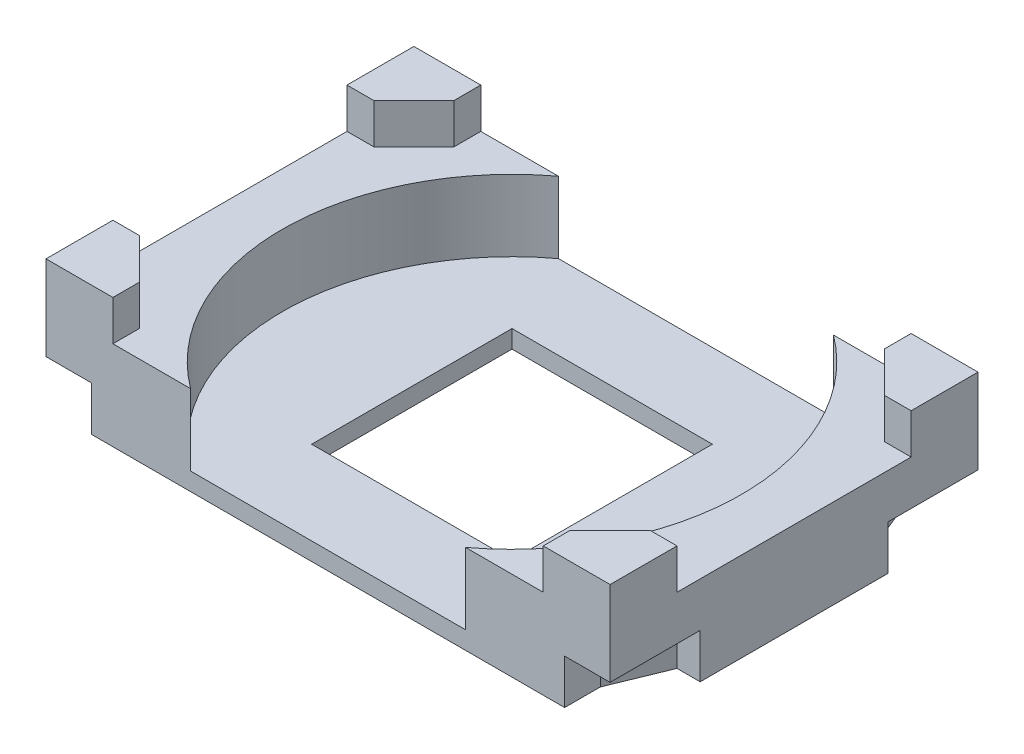
SolidWorks part; units mm, degrees
ref_plane "Спереди" through (0, 0, 0) normal (0, 0, 1) x (1, 0, 0)
ref_plane "Сверху" through (0, 0, 0) normal (0, 1, 0) x (1, 0, 0)
ref_plane "Справа" through (0, 0, 0) normal (1, 0, 0) x (0, 0, -1)
ref_plane "Плоскость4" through (0, 102.196, 0) normal (0, 1, 0) x (1, 0, 0)
sketch "Эскиз1" plane through (0, 102.196, 0) normal (0, 1, 0) x (1, 0, 0)
  line L20 (42.3449, -67.059) -> (42.3449, -111.9872)
  line L21 (42.3449, -111.9872) -> (87.2731, -111.9872)
  line L22 (87.2731, -111.9872) -> (87.2731, -67.059)
  line L23 (87.2731, -67.059) -> (42.3449, -67.059)
  line L24 (6.759, -68.4731) -> (1.559, -68.4731)
  line L25 (11.759, -56.2731) -> (11.759, -48.2731)
  line L27 (122.859, -110.5731) -> (128.059, -110.5731)
  line L28 (128.059, -110.5731) -> (128.059, -68.4731)
  line L29 (6.759, -68.4731) -> (11.759, -56.2731)
  line L30 (128.059, -68.4731) -> (122.859, -68.4731)
  line L31 (122.859, -68.4731) -> (117.859, -56.2731)
  line L32 (117.859, -56.2731) -> (117.859, -48.2731)
  line L33 (117.859, -48.2731) -> (11.759, -48.2731)
  line L34 (6.759, -110.5731) -> (1.559, -110.5731)
  line L35 (117.859, -122.7731) -> (117.859, -130.7731)
  line L36 (117.859, -122.7731) -> (122.859, -110.5731)
  line L37 (1.559, -110.5731) -> (1.559, -68.4731)
  line L39 (6.759, -110.5731) -> (11.759, -122.7731)
  line L40 (11.759, -122.7731) -> (11.759, -130.7731)
  line L41 (11.759, -130.7731) -> (117.859, -130.7731)
extrude "Бобышка-Вытянуть1" add sketch "Эскиз1" along normal blind 4
ref_plane "Плоскость5" through (0, 106.196, 0) normal (0, 1, 0) x (1, 0, 0)
sketch "Эскиз2" plane through (0, 106.196, 0) normal (0, 1, 0) x (1, 0, 0)
  line L18 (-8.25, -130.7731) -> (8.25, -130.7731) construction
  line L24 (95.6422, -130.7731) -> (117.859, -130.7731)
  line L25 (117.859, -130.7731) -> (117.859, -122.7731)
  line L26 (117.859, -122.7731) -> (122.859, -110.5731)
  line L27 (122.859, -110.5731) -> (128.059, -110.5731)
  line L28 (128.059, -110.5731) -> (128.059, -68.4731)
  line L29 (128.059, -68.4731) -> (122.859, -68.4731)
  line L30 (122.859, -68.4731) -> (117.859, -56.2731)
  line L31 (117.859, -56.2731) -> (117.859, -48.2731)
  line L32 (117.859, -48.2731) -> (95.6422, -48.2731)
  line L33 (33.9758, -48.2731) -> (11.759, -48.2731)
  line L34 (11.759, -48.2731) -> (11.759, -56.2731)
  line L35 (11.759, -56.2731) -> (6.759, -68.4731)
  line L36 (6.759, -68.4731) -> (1.559, -68.4731)
  line L37 (1.559, -68.4731) -> (1.559, -110.5731)
  line L38 (1.559, -110.5731) -> (6.759, -110.5731)
  line L39 (6.759, -110.5731) -> (11.759, -122.7731)
  line L40 (11.759, -122.7731) -> (11.759, -130.7731)
  line L41 (11.759, -130.7731) -> (33.9758, -130.7731)
  arc A1 (95.6422, -48.2731) -> (95.6422, -130.7731) centre (64.809, -89.5231) cw
  arc A2 (33.9758, -48.2731) -> (33.9758, -130.7731) centre (64.809, -89.5231) ccw
  point P29 (0, 0)
extrude "Бобышка-Вытянуть2" add sketch "Эскиз2" along normal blind 6
ref_plane "Плоскость6" through (0, 112.196, 0) normal (0, 1, 0) x (1, 0, 0)
sketch "Эскиз3" plane through (0, 112.196, 0) normal (0, 1, 0) x (1, 0, 0)
  line L0 (1.559, -130.7731) -> (1.559, -48.2731)
  line L1 (1.559, -48.2731) -> (33.9758, -48.2731)
  line L2 (1.559, -130.7731) -> (33.9758, -130.7731)
  line L3 (95.6422, -48.2731) -> (128.059, -48.2731)
  line L4 (128.059, -48.2731) -> (128.059, -130.7731)
  line L5 (128.059, -130.7731) -> (95.6422, -130.7731)
  arc A1 (95.6422, -48.2731) -> (95.6422, -130.7731) centre (64.809, -89.5231) cw
  arc A2 (33.9758, -48.2731) -> (33.9758, -130.7731) centre (64.809, -89.5231) ccw
  point P18 (0, 0)
  point P19 (0, 0)
  point P20 (0, 0)
  point P21 (0, 0)
extrude "Бобышка-Вытянуть3" add sketch "Эскиз3" along normal blind 10
ref_plane "Плоскость7" through (0, 122.196, 0) normal (0, 1, 0) x (1, 0, 0)
sketch "Эскиз4" plane through (0, 122.196, 0) normal (0, 1, 0) x (1, 0, 0)
  line L0 (1.559, -48.2731) -> (16.559, -48.2731)
  line L1 (33.9758, -48.2731) -> (1.559, -48.2731) construction
  line L2 (16.559, -48.2731) -> (16.559, -54.2731)
  line L3 (1.559, -48.2731) -> (1.559, -63.2731)
  line L4 (1.559, -48.2731) -> (1.559, -130.7731) construction
  line L5 (1.559, -63.2731) -> (7.559, -63.2731)
  line L6 (7.559, -63.2731) -> (16.559, -54.2731)
  line L7 (128.059, -48.2731) -> (113.059, -48.2731)
  line L8 (128.059, -48.2731) -> (95.6422, -48.2731) construction
  line L9 (113.059, -48.2731) -> (113.059, -54.2731)
  line L10 (128.059, -48.2731) -> (128.059, -63.2731)
  line L11 (128.059, -130.7731) -> (128.059, -48.2731) construction
  line L12 (128.059, -63.2731) -> (122.059, -63.2731)
  line L13 (122.059, -63.2731) -> (113.059, -54.2731)
  line L14 (128.059, -130.7731) -> (128.059, -115.7731)
  line L15 (128.059, -115.7731) -> (122.059, -115.7731)
  line L16 (128.059, -130.7731) -> (113.059, -130.7731)
  line L17 (95.6422, -130.7731) -> (128.059, -130.7731) construction
  line L18 (113.059, -130.7731) -> (113.059, -124.7731)
  line L19 (113.059, -124.7731) -> (122.059, -115.7731)
  line L20 (1.559, -130.7731) -> (1.559, -115.7731)
  line L21 (1.559, -115.7731) -> (7.559, -115.7731)
  line L22 (1.559, -130.7731) -> (16.559, -130.7731)
  line L23 (1.559, -130.7731) -> (33.9758, -130.7731) construction
  line L24 (16.559, -130.7731) -> (16.559, -124.7731)
  line L25 (16.559, -124.7731) -> (7.559, -115.7731)
  point P31 (0, 0)
  point P37 (0, 0)
  point P38 (0, 0)
  point P39 (0, 0)
extrude "Бобышка-Вытянуть4" add sketch "Эскиз4" along normal blind 9
